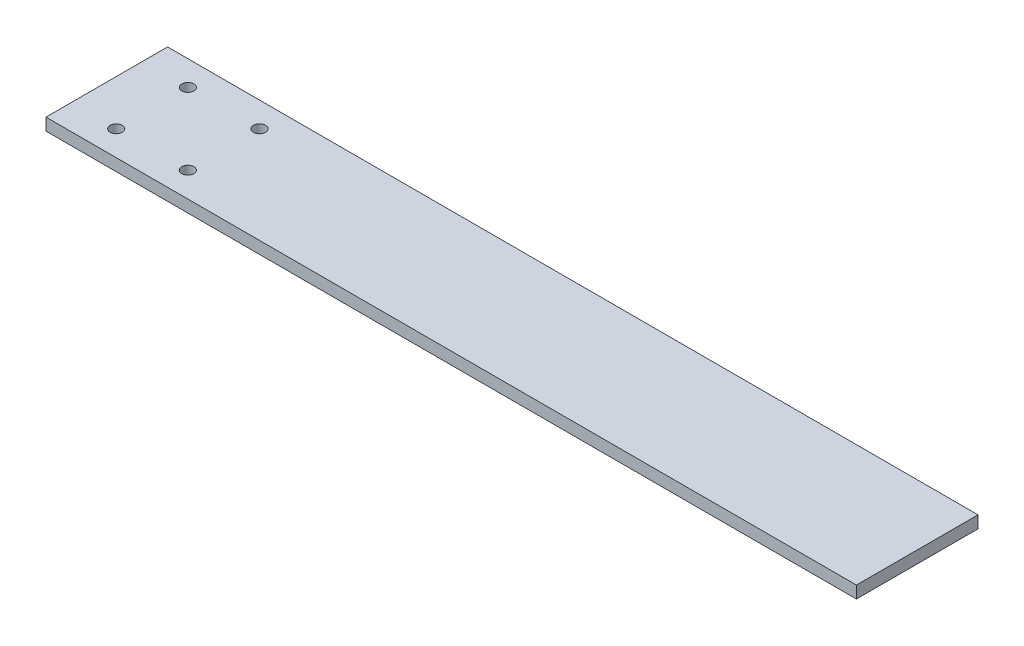
SolidWorks part; units mm, degrees
ref_plane "Front Plane" through (0, 0, 0) normal (0, 0, 1) x (1, 0, 0)
ref_plane "Top Plane" through (0, 0, 0) normal (0, 1, 0) x (1, 0, 0)
ref_plane "Right Plane" through (0, 0, 0) normal (1, 0, 0) x (0, 0, -1)
sketch "Sketch1" plane through (0, 0, 0) normal (0, 1, 0) x (1, 0, 0)
  line L0 (0, 0) -> (-100, 0) construction
  line L1 (-100, 15) -> (100, 15)
  line L2 (-100, 15) -> (-100, -15)
  line L3 (-100, -15) -> (100, -15)
  line L4 (100, 15) -> (100, -15)
  line L5 (-100, 15) -> (100, -15) construction
  line L6 (-100, -15) -> (100, 15) construction
  line L7 (-80, 0) -> (-88.8388, -8.8388) construction
  circle A0 centre (-80, 0) radius 12.5 construction
  circle A5 centre (-88.8388, -8.8388) radius 1.5
  circle A6 centre (-88.8388, 8.8388) radius 1.5
  circle A7 centre (-71.1612, 8.8388) radius 1.5
  circle A8 centre (-71.1612, -8.8388) radius 1.5
  point P0 (0, 0)
  point P12 (-80, 0)
  point P21 (-80, 0)
  point P22 (-80, 0)
  dimension "D3" = 25
  dimension "D4" = 20
  dimension "D5" = 3
  dimension "D6" = 45
  dimension "D1" = 30
  dimension "D2" = 200
  dimension "D7" = 4
extrude "Boss-Extrude1" add sketch "Sketch1" along normal blind 3
